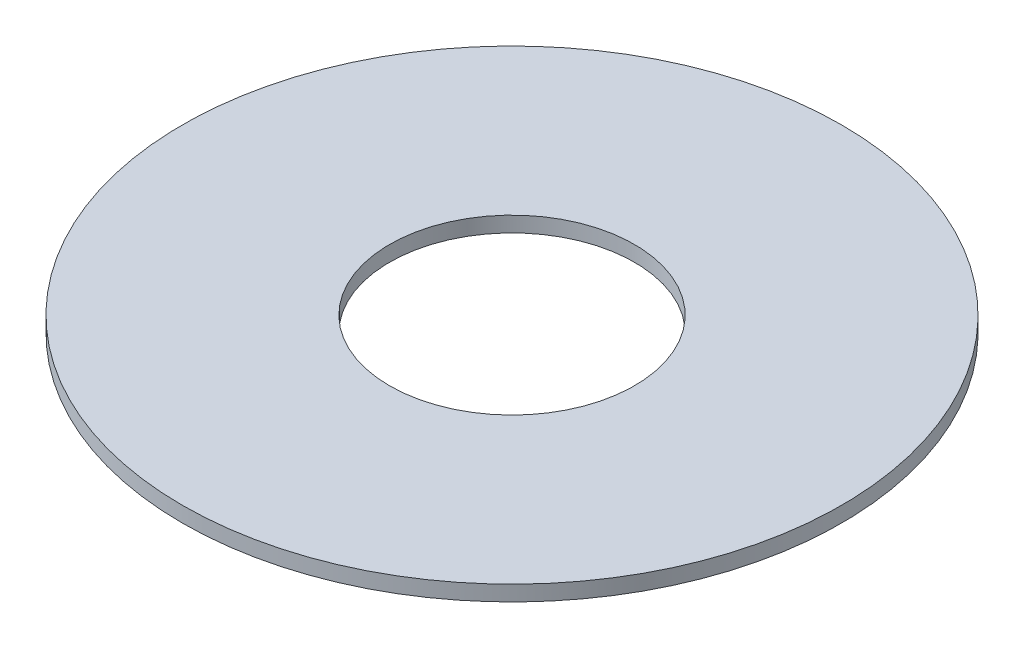
SolidWorks part; units mm, degrees
material "PTFE (general)"
ref_plane "Front Plane" through (0, 0, 0) normal (0, 0, 1) x (1, 0, 0)
ref_plane "Top Plane" through (0, 0, 0) normal (0, 1, 0) x (1, 0, 0)
ref_plane "Right Plane" through (0, 0, 0) normal (1, 0, 0) x (0, 0, -1)
sketch "Sketch1" plane through (0, 0, 0) normal (0, 1, 0) x (1, 0, 0)
  circle A0 centre (0, 0) radius 42.725
  circle A1 centre (0, 0) radius 15.875
  dimension "D1" = 31.75
  dimension "D2" = 85.45
extrude "Boss-Extrude1" add sketch "Sketch1" along normal blind 2
